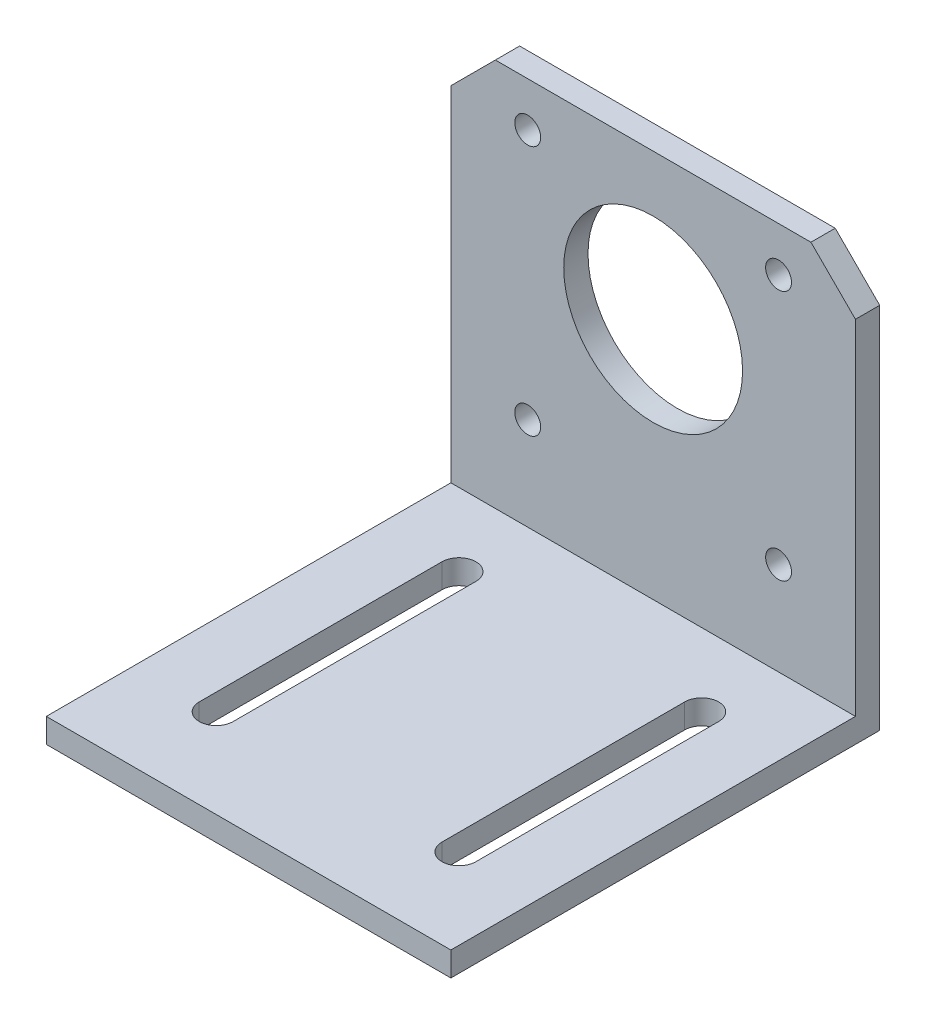
SolidWorks part; units mm, degrees
ref_plane "前视基准面" through (0, 0, 0) normal (0, 0, 1) x (1, 0, 0)
ref_plane "上视基准面" through (0, 0, 0) normal (0, 1, 0) x (1, 0, 0)
ref_plane "右视基准面" through (0, 0, 0) normal (1, 0, 0) x (0, 0, -1)
other "Configuration Table"
sketch "草图1" plane through (0, 0, 0) normal (1, 0, 0) x (0, 0, -1)
  line L1 (0, 0) -> (53, 0)
  line L2 (0, 0) -> (0, 51)
  line L3 (0, 51) -> (53, 51)
  line L4 (53, 0) -> (53, 51)
  dimension "D1" = 51
  dimension "D2" = 53
extrude "凸台-拉伸1" add sketch "草图1" along normal blind 50
sketch "草图2" plane through (0, 0, 0) normal (-1, 0, 0) x (0, 0, 1)
  line L1 (-50, 51) -> (-50, 3)
  line L2 (-53, 51) -> (0, 51) construction
  line L3 (-50, 3) -> (0, 3)
  line L4 (0, 51) -> (0, 0) construction
  line L5 (0, 3) -> (0, 51)
  line L6 (0, 51) -> (-50, 51)
  line L7 (-53, 0) -> (-53, 51) construction
  line L8 (0, 0) -> (-53, 0) construction
  dimension "D1" = 3
  dimension "D2" = 3
extrude "切除-拉伸1" cut sketch "草图2" against normal blind 50
sketch "草图3" plane through (0, 3, 0) normal (0, 1, 0) x (1, 0, 0)
  line L2 (7.9, 41) -> (7.9, 11)
  line L4 (12.1, 41) -> (12.1, 11)
  line L6 (37.9, 41) -> (37.9, 11)
  line L8 (42.1, 41) -> (42.1, 11)
  line L10 (50, 50) -> (50, 0) construction
  arc A0 (7.9, 41) -> (12.1, 41) centre (10, 41) cw
  arc A1 (37.9, 41) -> (42.1, 41) centre (40, 41) cw
  arc A2 (42.1, 11) -> (37.9, 11) centre (40, 11) cw
  arc A3 (12.1, 11) -> (7.9, 11) centre (10, 11) cw
  dimension "D1" = 30
  dimension "D2" = 30
  dimension "D3" = 4.2
  dimension "D4" = 4.2
  dimension "D5" = 25.8
  dimension "D7" = 7.9
extrude "切除-拉伸2" cut sketch "草图3" against normal mid plane 50
sketch "草图4" plane through (0, 0, -50) normal (0, 0, 1) x (1, 0, 0)
  line L0 (50, 3) -> (0, 3) construction
  line L1 (0, 51) -> (0, 3) construction
  line L3 (50, 51) -> (0, 51) construction
  line L4 (5.5, 51) -> (0, 45.5)
  line L5 (0, 45.5) -> (0, 51)
  line L6 (0, 51) -> (5.5, 51)
  line L7 (44.5, 51) -> (50, 45.5)
  line L8 (50, 51) -> (50, 3) construction
  line L9 (50, 45.5) -> (50, 51)
  line L10 (50, 51) -> (44.5, 51)
  circle A0 centre (25, 33) radius 11.05
  circle A1 centre (9.5, 45.5) radius 1.6
  circle A2 centre (40.5, 45.5) radius 1.6
  circle A4 centre (9.5, 14.5) radius 1.6
  circle A5 centre (40.5, 14.5) radius 1.6
  dimension "D1" = 30
  dimension "D2" = 22.1
  dimension "D4" = 3.2
  dimension "D5" = 3.2
  dimension "D6" = 3.2
  dimension "D7" = 3.2
  dimension "D8" = 31
  dimension "D9" = 31
  dimension "D10" = 31
  dimension "D11" = 9.5
  dimension "D12" = 5.5
  dimension "D3" = 25
  dimension "D13" = 5.5
  dimension "D14" = 5.5
  dimension "D15" = 5.5
  dimension "D16" = 5.5
extrude "切除-拉伸3" cut sketch "草图4" against normal blind 50
